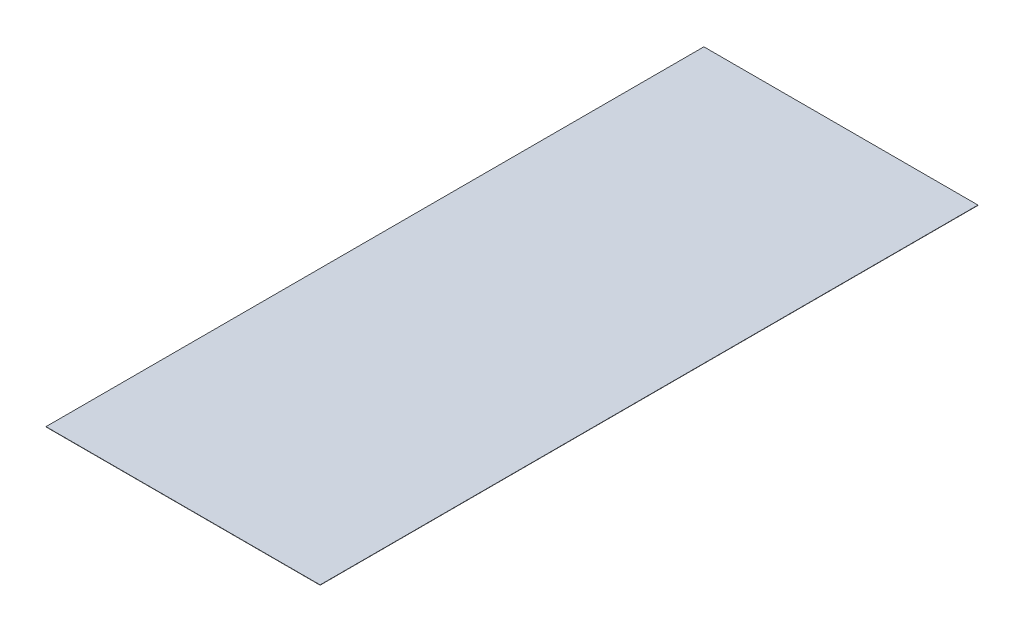
SolidWorks part; units mm, degrees
ref_plane "Спереди" through (0, 0, 0) normal (0, 0, 1) x (1, 0, 0)
ref_plane "Сверху" through (0, 0, 0) normal (0, 1, 0) x (1, 0, 0)
ref_plane "Справа" through (0, 0, 0) normal (1, 0, 0) x (0, 0, -1)
other "Configuration Table"
sketch "Эскиз1" plane through (0, 0, 0) normal (0, 1, 0) x (1, 0, 0)
  line L1 (500, 1200) -> (-500, 1200)
  line L2 (500, 1200) -> (500, -1200)
  line L3 (500, -1200) -> (-500, -1200)
  line L4 (-500, 1200) -> (-500, -1200)
  line L5 (500, 1200) -> (-500, -1200) construction
  line L6 (500, -1200) -> (-500, 1200) construction
  point P0 (0, 0)
extrude "Бобышка-Вытянуть1" add sketch "Эскиз1" along normal blind 1
